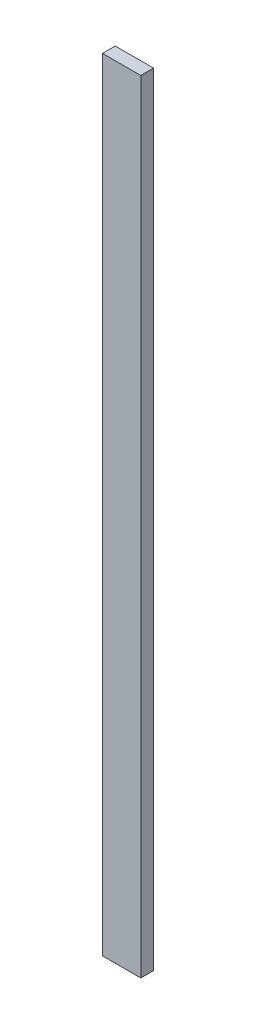
SolidWorks part; units mm, degrees
ref_plane "Front Plane" through (0, 0, 0) normal (0, 0, 1) x (1, 0, 0)
ref_plane "Top Plane" through (0, 0, 0) normal (0, 1, 0) x (1, 0, 0)
ref_plane "Right Plane" through (0, 0, 0) normal (1, 0, 0) x (0, 0, -1)
sketch "Sketch1" plane through (0, 0, 0) normal (0, 0, 1) x (1, 0, 0)
  line L1 (0, 0) -> (12, 0)
  line L2 (0, 0) -> (0, 245)
  line L3 (0, 245) -> (12, 245)
  line L4 (12, 0) -> (12, 245)
  dimension "D1" = 12
  dimension "D2" = 245
extrude "Profile" add sketch "Sketch1" along normal blind 4
equation "\"Profile_Depth\" = 4mm"
equation "\"D1@Profile\" = \"Profile_Depth\""
equation "\"Profile_Sketch_1\" = 12mm"
equation "\"D1@Sketch1\" = \"Profile_Sketch_1\""
equation "\"Profile_Sketch_2\" = 245mm"
equation "\"D2@Sketch1\" = \"Profile_Sketch_2\""
equation "\"EnvelopeWidth\" = 12mm"
equation "\"EnvelopeHeight\" = 245mm"
